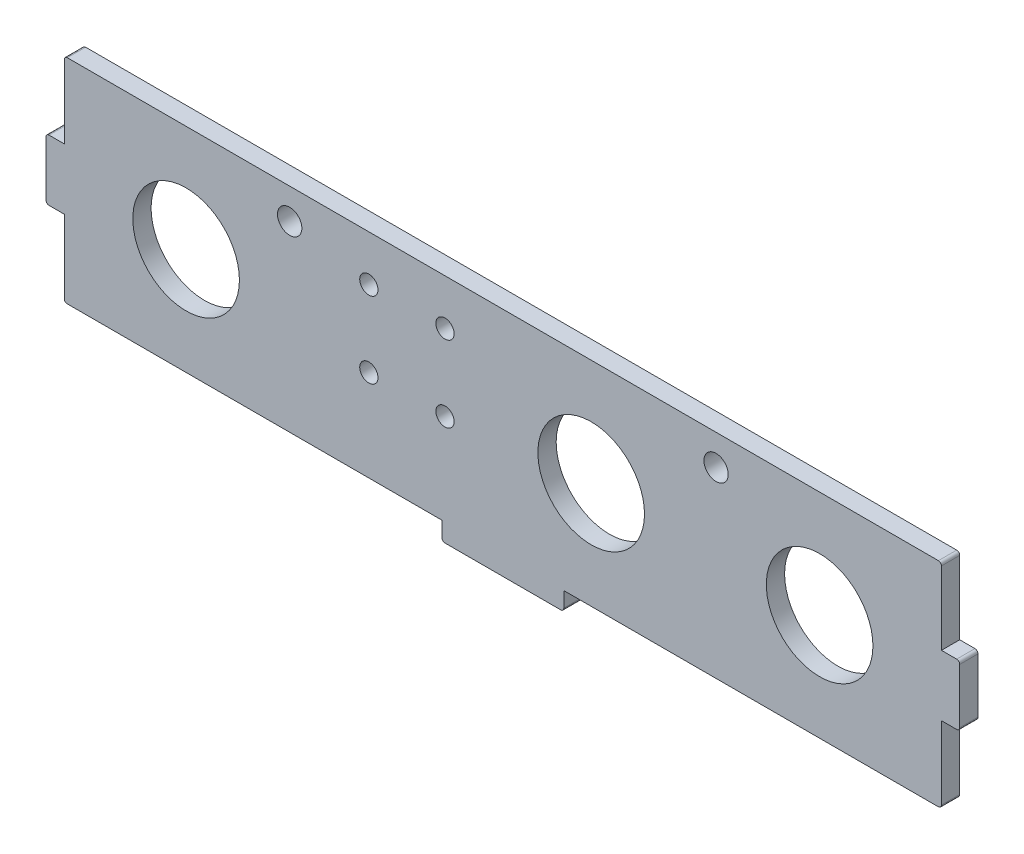
SolidWorks part; units mm, degrees
material "Beech"
ref_plane "Спереди" through (0, 0, 0) normal (0, 0, 1) x (1, 0, 0)
ref_plane "Сверху" through (0, 0, 0) normal (0, 1, 0) x (1, 0, 0)
ref_plane "Справа" through (0, 0, 0) normal (1, 0, 0) x (0, 0, -1)
sketch "Sketch1" plane through (0, 0, 0) normal (0, 0, 1) x (1, 0, 0)
  line L1 (0, 0) -> (300, 0)
  line L2 (0, 0) -> (0, 70)
  line L3 (0, 70) -> (300, 70)
  line L4 (300, 0) -> (300, 70)
  dimension "D1" = 70
  dimension "D2" = 300
extrude "front" add sketch "Sketch1" against normal blind 6
sketch "Sketch2" plane through (0, 0, 0) normal (0, 0, 1) x (1, 0, 0)
  line L0 (6, 70) -> (6, 45)
  line L1 (300, 70) -> (0, 70) construction
  line L2 (6, 45) -> (0, 45)
  line L3 (0, 70) -> (0, 0) construction
  line L4 (0, 25) -> (6, 25)
  line L5 (6, 25) -> (6, 0)
  line L6 (0, 0) -> (300, 0) construction
  line L7 (0, 45) -> (0, 25)
  line L8 (6, 70) -> (0, 70)
  line L9 (0, 70) -> (0, 45)
  line L10 (80, 60) -> (220, 60) construction
  line L11 (0, 25) -> (0, 0)
  line L12 (0, 0) -> (6, 0)
  line L13 (294, 70) -> (294, 45)
  line L14 (294, 45) -> (300, 45)
  line L15 (300, 0) -> (300, 70) construction
  line L16 (300, 45) -> (300, 70)
  line L17 (300, 70) -> (294, 70)
  line L18 (300, 25) -> (294, 25)
  line L19 (294, 25) -> (294, 0)
  line L20 (294, 0) -> (300, 0)
  line L21 (300, 0) -> (300, 25)
  circle A0 centre (80, 60) radius 4
  circle A1 centre (220, 60) radius 4
  point P32 (150, 70)
  point P33 (150, 60)
  line M1 (0, 70) -> (0, 0)
  line M2 (0, 0) -> (300, 0)
  line M4 (300, 70) -> (0, 70)
  dimension "D4" = 8
  dimension "D1" = 6
  dimension "D2" = 20
  dimension "D3" = 140
  dimension "D5" = 10
extrude "mount" cut sketch "Sketch2" against normal through all contours L2 L0 M4 M1 | L5 L4 M1 M2 | L16 L17 L13 L14 | L21 L18 L19 L20 | A0 | A1
sketch "Sketch3" plane through (0, 0, 0) normal (0, 0, 1) x (1, 0, 0)
  line L0 (6, 0) -> (294, 0) construction
  line L1 (130, 0) -> (170, 0)
  line L2 (130, 0) -> (130, -6)
  line L3 (130, -6) -> (170, -6)
  line L4 (170, 0) -> (170, -6)
  line L5 (294, 70) -> (6, 70) construction
  point P6 (150, -6)
  point P7 (150, 70)
  dimension "D1" = 6
  dimension "D2" = 40
extrude "Boss-Extrude1" add sketch "Sketch3" against normal up to surface (6 mm away) up to face at (224, 60, -6)
fillet "fillet" radius 1 10 edges at (0, 45, -3) (0, 25, -3) (294, 0, -3) (300, 25, -3) (300, 45, -3) (294, 70, -3) (6, 0, -3) (6, 70, -3) (170, -6, -3) (130, -6, -3)
sketch "Sketch4" plane through (0, 0, 0) normal (0, 0, 1) x (1, 0, 0)
  line L0 (106, 55) -> (131, 55) construction
  line L1 (131, 55) -> (131, 30) construction
  line L2 (131, 30) -> (106, 30) construction
  line L3 (106, 30) -> (106, 55) construction
  line L4 (293, 70) -> (7, 70) construction
  line L5 (6, 69) -> (6, 45) construction
  circle A0 centre (106, 55) radius 3
  circle A1 centre (131, 55) radius 3
  circle A2 centre (106, 30) radius 3
  circle A3 centre (131, 30) radius 3
  dimension "D1" = 6
  dimension "D2" = 25
  dimension "D3" = 15
  dimension "D4" = 100
extrude "Cut-Extrude1" cut sketch "Sketch4" against normal through all
sketch "Sketch5" plane through (0, 0, 0) normal (0, 0, 1) x (1, 0, 0)
  line L0 (294, 25) -> (294, 1) construction
  line L1 (6, 25) -> (6, 1) construction
  line L2 (7, 0) -> (130, 0) construction
  circle A0 centre (46, 35) radius 17.5
  circle A1 centre (179, 35) radius 17.5
  circle A2 centre (254, 35) radius 17.5
  dimension "D1" = 35
  dimension "D2" = 40
  dimension "D3" = 75
  dimension "D4" = 40
  dimension "D5" = 35
extrude "lite" cut sketch "Sketch5" against normal up to next
